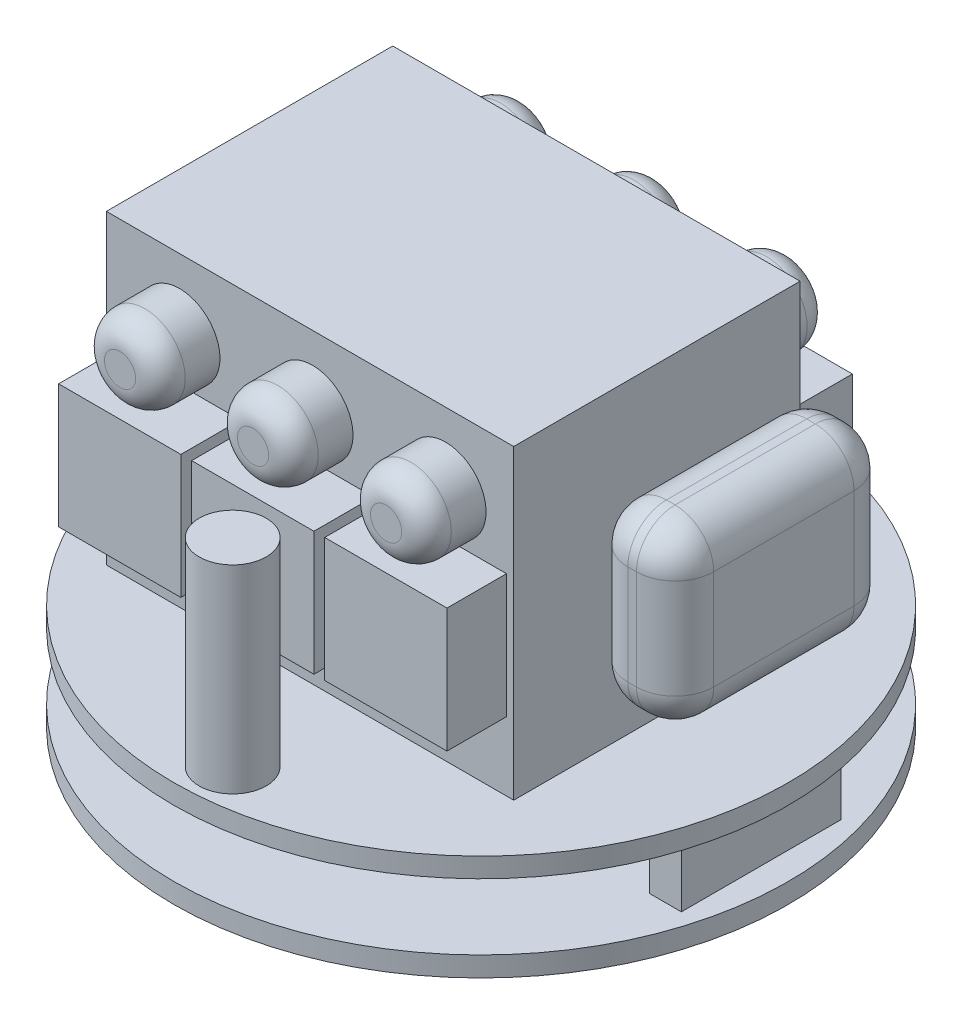
SolidWorks part; units mm, degrees
other "Markup1"
sketch "Sketch11" plane through (-24.257, 0, 24.257) normal (-0.0476, -0.9947, 0.0911) x (-0.8658, 0.0866, 0.4928)
ref_plane "Front Plane" through (0, 0, 0) normal (0, 0, 1) x (1, 0, 0)
ref_plane "Top Plane" through (0, 0, 0) normal (0, 1, 0) x (1, 0, 0)
ref_plane "Right Plane" through (0, 0, 0) normal (1, 0, 0) x (0, 0, -1)
sketch "Sketch1" plane through (0, 0, 0) normal (0, 1, 0) x (1, 0, 0)
  circle A0 centre (0, 0) radius 24.257
  dimension "D1" = 48.514
extrude "Boss-Extrude1" add sketch "Sketch1" along normal blind 1.5748
sketch "Sketch2" plane through (0, 1.5748, 0) normal (0, 1, 0) x (1, 0, 0)
  line L0 (0, 0) -> (-24.257, 0) construction
  line L1 (-22.1107, 6.2992) -> (-19.5961, 6.2992)
  line L2 (-22.1107, 6.2992) -> (-22.1107, -6.2992)
  line L3 (-22.1107, -6.2992) -> (-19.5961, -6.2992)
  line L4 (-19.5961, 6.2992) -> (-19.5961, -6.2992)
  line L5 (0, 0) -> (0, 24.257) construction
  line L6 (19.5961, 6.2992) -> (19.5961, -6.2992)
  line L7 (22.1107, -6.2992) -> (19.5961, -6.2992)
  line L8 (22.1107, 6.2992) -> (22.1107, -6.2992)
  line L9 (22.1107, 6.2992) -> (19.5961, 6.2992)
  circle A0 centre (0, 0) radius 24.257 construction
  point P9 (-22.1107, 0)
  dimension "D1" = 12.5984
  dimension "D2" = 2.5146
  dimension "D3" = 2.1463
extrude "Boss-Extrude2" add sketch "Sketch2" along normal blind 5.207
sketch "Sketch3" plane through (0, 6.7818, 0) normal (0, 1, 0) x (1, 0, 0)
  circle A0 centre (0, 0) radius 24.257 construction
  circle A1 centre (0, 0) radius 24.257
extrude "Boss-Extrude3" add sketch "Sketch3" along normal blind 1.5494
sketch "Sketch4" plane through (0, 8.3312, 0) normal (0, 1, 0) x (1, 0, 0)
  line L0 (0, 0) -> (24.257, 0) construction
  line L1 (-17.5387, -12.0396) -> (14.6177, -12.0396)
  line L2 (-17.5387, -12.0396) -> (-17.5387, 10.5664)
  line L3 (-17.5387, 10.5664) -> (14.6177, 10.5664)
  line L4 (14.6177, -12.0396) -> (14.6177, 10.5664)
  line L5 (0, 0) -> (0, 24.257) construction
  circle A0 centre (0, 0) radius 24.257 construction
  dimension "D1" = 22.606
  dimension "D2" = 32.1564
  dimension "D3" = 13.6906
  dimension "D4" = 9.6393
extrude "Boss-Extrude4" add sketch "Sketch4" along normal blind 24.1808
sketch "Sketch5" plane through (0, 0, 12.0396) normal (0, 0, 1) x (1, 0, 0)
  line L0 (14.6177, 32.512) -> (14.6177, 8.3312) construction
  line L1 (14.0462, 13.7541) -> (4.3942, 13.7541)
  line L2 (14.0462, 13.7541) -> (14.0462, 23.5331)
  line L3 (14.0462, 23.5331) -> (4.3942, 23.5331)
  line L4 (4.3942, 13.7541) -> (4.3942, 23.5331)
  line L5 (-17.5387, 32.512) -> (14.6177, 32.512) construction
  line L6 (9.2456, 26.9367) -> (12.4333, 26.9367) construction
  line L7 (9.2456, 26.9367) -> (9.2456, 30.1244) construction
  circle A0 centre (9.2456, 26.9367) radius 3.1877
  point P10 (0, 0)
  dimension "D5" = 6.3754
  dimension "D1" = 9.779
  dimension "D2" = 9.652
  dimension "D3" = 0.5715
  dimension "D4" = 8.9789
  dimension "D6" = 2.1844
  dimension "D7" = 2.3876
extrude "Boss-Extrude5" add sketch "Sketch5" along normal blind 4.699
ref_plane "Plane1" through (0, 0, 0.7366) normal (0, 0, 1) x (1, 0, 0)
pattern_linear "LPattern1" count 3 spacing 10.5029 along (-1, 0, 0) of "Boss-Extrude5"
mirror "Mirror1" about plane through (0, 0, 0.7366) normal (0, 0, 1) of "LPattern1", "Boss-Extrude5"
fillet "Fillet1" radius 1.9558 6 edges at (-8.5725, 26.9367, -15.2654) (1.9304, 26.9367, -15.2654) (12.4333, 26.9367, -15.2654) (12.4333, 26.9367, 16.7386) (1.9304, 26.9367, 16.7386) (-8.5725, 26.9367, 16.7386)
sketch "Sketch6" plane through (0, 8.3312, 0) normal (0, 1, 0) x (1, 0, 0)
  line L0 (0, 0) -> (0, -24.257) construction
  line L1 (1.2256, -20.8344) -> (1.2256, -23.4823) construction
  line L2 (1.2256, -20.8344) -> (-1.4224, -20.8344) construction
  line L3 (0, 0) -> (24.257, 0) construction
  circle A0 centre (1.2256, -20.8344) radius 2.6479
  circle A1 centre (0, 0) radius 24.257 construction
  dimension "D1" = 5.2959
  dimension "D2" = 0.7747
  dimension "D3" = 25.6794
extrude "Boss-Extrude6" add sketch "Sketch6" along normal blind 15.6591
sketch "Sketch7" plane through (14.6177, 0, 0) normal (1, 0, 0) x (0, 0, -1)
  line L0 (-12.0396, 32.512) -> (10.5664, 32.512) construction
  line L1 (-6.0833, 11.9126) -> (11.0871, 11.9126)
  line L2 (-6.0833, 11.9126) -> (-6.0833, 25.8826)
  line L3 (-6.0833, 25.8826) -> (11.0871, 25.8826)
  line L4 (11.0871, 11.9126) -> (11.0871, 25.8826)
  line L5 (-16.7386, 13.7541) -> (-16.7386, 23.5331) construction
  dimension "D1" = 17.1704
  dimension "D2" = 13.97
  dimension "D3" = 6.6294
  dimension "D4" = 10.6553
extrude "Boss-Extrude7" add sketch "Sketch7" along normal blind 6.7818 separate body
fillet "Fillet2" radius 3.048 12 edges at (18.0086, 11.9126, 6.0833) (21.3995, 11.9126, -2.5019) (18.0086, 11.9126, -11.0871) (14.6177, 11.9126, -2.5019) (14.6177, 18.8976, -11.0871) (21.3995, 18.8976, 6.0833) (21.3995, 18.8976, -11.0871) (18.0086, 25.8826, -11.0871) (21.3995, 25.8826, -2.5019) (18.0086, 25.8826, 6.0833) (14.6177, 18.8976, 6.0833) (14.6177, 25.8826, -2.5019)
sketch "Sketch9" plane through (0, 0, 0) normal (0, -1, 0) x (1, 0, 0)
  circle A0 centre (0, 0) radius 5.5372
  dimension "D1" = 11.0744
extrude "Cut-Extrude1" cut sketch "Sketch9" against normal blind 19.8882
sketch "Sketch12" plane through (0, 0, 0) normal (0, -1, 0) x (1, 0, 0)
  line L0 (-620.3037, 308.3106) -> (-152.9704, 308.3106) construction
  line L1 (-372.0372, -542.9772) -> (-372.0372, -75.6438) construction
